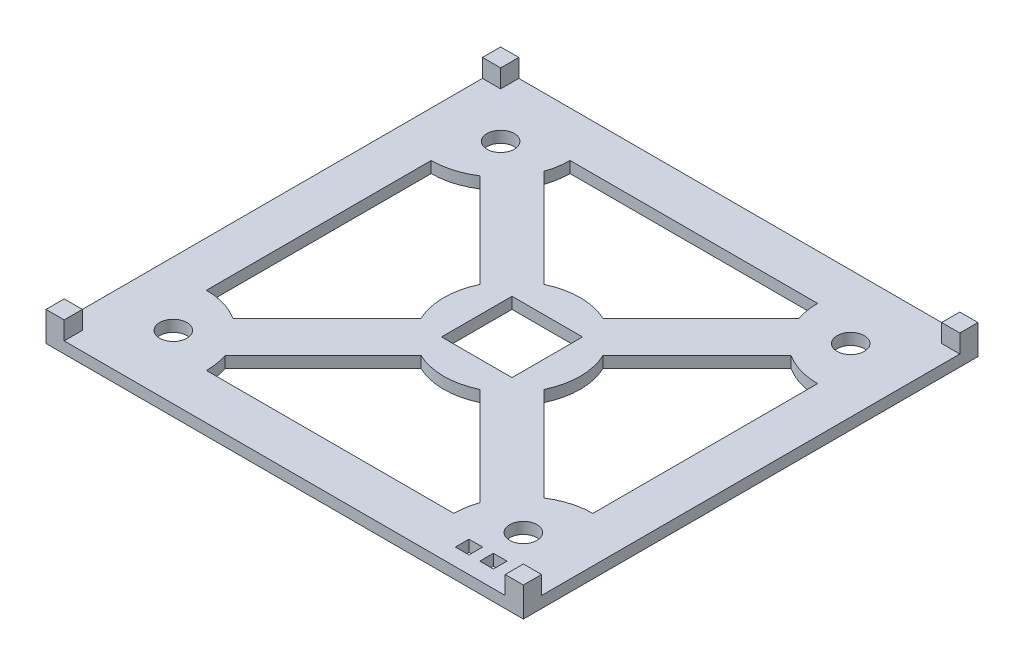
SolidWorks part; units mm, degrees
ref_plane "Front Plane" through (0, 0, 0) normal (0, 0, 1) x (1, 0, 0)
ref_plane "Top Plane" through (0, 0, 0) normal (0, 1, 0) x (1, 0, 0)
ref_plane "Right Plane" through (0, 0, 0) normal (1, 0, 0) x (0, 0, -1)
sketch "Sketch1" plane through (0, 0, 0) normal (0, 1, 0) x (1, 0, 0)
  line L1 (-52.5, -50) -> (52.5, -50)
  line L2 (-52.5, -50) -> (-52.5, 50)
  line L3 (-52.5, 50) -> (52.5, 50)
  line L4 (52.5, -50) -> (52.5, 50)
  line L5 (-52.5, -50) -> (52.5, 50) construction
  line L6 (-52.5, 50) -> (52.5, -50) construction
  point P0 (0, 0)
  dimension "D1" = 105
  dimension "D2" = 100
extrude "Boss-Extrude1" add sketch "Sketch1" along normal blind 2.5
sketch "Sketch3" plane through (0, 2.5, 0) normal (0, 1, 0) x (1, 0, 0)
  line L0 (-69.1295, 0) -> (69.1295, 0)
  line L1 (-52.5, 50) -> (-48.5, 50)
  line L2 (-52.5, 50) -> (-52.5, 46)
  line L3 (-52.5, 46) -> (-48.5, 46)
  line L4 (-48.5, 50) -> (-48.5, 46)
  line L5 (52.5, -50) -> (48.5, -50)
  line L6 (52.5, 50) -> (48.5, 50)
  line L7 (52.5, 50) -> (52.5, 46)
  line L8 (52.5, 46) -> (48.5, 46)
  line L9 (48.5, 50) -> (48.5, 46)
  line L10 (52.5, -50) -> (52.5, -46)
  line L11 (52.5, -46) -> (48.5, -46)
  line L12 (48.5, -50) -> (48.5, -46)
  line L13 (-48.5, -50) -> (-48.5, -46)
  line L14 (-52.5, -50) -> (-48.5, -50)
  line L15 (-52.5, -50) -> (-52.5, -46)
  line L16 (-52.5, -46) -> (-48.5, -46)
  point P9 (0, 0)
  line M14 (52.5, -50) -> (52.5, 50)
  line M15 (52.5, 50) -> (-52.5, 50)
  line M16 (-52.5, 50) -> (-52.5, -50)
  line M17 (-52.5, -50) -> (52.5, -50)
  dimension "D1" = 4
extrude "Boss-Extrude2" add sketch "Sketch3" along normal blind 4 contours L4 L3 M15 M16 | L9 L8 M15 M14 | L12 L11 M17 M14 | L16 L13 M16 M17
sketch "Sketch4" plane through (0, 2.5, 0) normal (0, 1, 0) x (1, 0, 0)
sketch "Sketch5" plane through (0, 2.5, 0) normal (0, 1, 0) x (1, 0, 0)
  line L1 (-42.5, -40) -> (42.5, -40)
  line L2 (-42.5, -40) -> (-42.5, 40)
  line L3 (-42.5, 40) -> (42.5, 40)
  line L4 (42.5, -40) -> (42.5, 40)
  line L5 (-42.5, -40) -> (42.5, 40) construction
  line L6 (-42.5, 40) -> (42.5, -40) construction
  line L7 (52.5, -46) -> (52.5, 46) construction
  line L8 (-48.5, -50) -> (48.5, -50) construction
  point P0 (0, 0)
  dimension "D1" = 10
  dimension "D2" = 10
extrude "Cut-Extrude2" cut sketch "Sketch5" against normal blind 4
sketch "Sketch6" plane through (0, 2.5, 0) normal (0, 1, 0) x (1, 0, 0)
  circle A0 centre (0, 0) radius 15
  dimension "D1" = 30
extrude "Boss-Extrude3" add sketch "Sketch6" against normal blind 2.5 separate body
sketch "Sketch7" plane through (0, 2.5, 0) normal (0, 1, 0) x (1, 0, 0)
  line L1 (-7.75, -7.75) -> (7.75, -7.75)
  line L2 (-7.75, -7.75) -> (-7.75, 7.75)
  line L3 (-7.75, 7.75) -> (7.75, 7.75)
  line L4 (7.75, -7.75) -> (7.75, 7.75)
  line L5 (-7.75, -7.75) -> (7.75, 7.75) construction
  line L6 (-7.75, 7.75) -> (7.75, -7.75) construction
  point P0 (0, 0)
  dimension "D1" = 15.5
  dimension "D2" = 15.5
extrude "Cut-Extrude3" cut sketch "Sketch7" against normal blind 2.5
sketch "Sketch8" plane through (0, 2.5, 0) normal (0, 1, 0) x (1, 0, 0)
  line L0 (42.5, -40) -> (42.5, 40) construction
  line L1 (42.5, 40) -> (-42.5, 40) construction
  line L2 (0, -54.2426) -> (0, 54.2426)
  line L3 (27.2201, 40) -> (42.5, 40)
  line L4 (42.5, 40) -> (42.5, 24.7201)
  line L5 (-63.2717, 0) -> (63.2717, 0)
  arc A0 (42.5, 24.7201) -> (27.2201, 40) centre (42.5, 40) cw
  arc A1 (-42.5, 24.7201) -> (-27.2201, 40) centre (-42.5, 40) ccw
  arc A2 (42.5, -24.7201) -> (27.2201, -40) centre (42.5, -40) ccw
  arc A3 (-42.5, -24.7201) -> (-27.2201, -40) centre (-42.5, -40) cw
  point P13 (0, 0)
  point P15 (0, 0)
  line M3 (-42.5, 40) -> (42.5, 40)
  line M4 (42.5, 40) -> (42.5, -40)
  line M5 (42.5, -40) -> (-42.5, -40)
  line M6 (-42.5, -40) -> (-42.5, 40)
extrude "Boss-Extrude4" add sketch "Sketch8" against normal blind 2.5 contours A3 M6 M5 | A1 M6 M3 | A0 M4 M3 | A2 M4 M5
sketch "Sketch9" plane through (0, 2.5, 0) normal (0, 1, 0) x (1, 0, 0)
  line L0 (7.75, -7.75) -> (38.0042, -38.0042)
  line L2 (-7.75, -7.75) -> (-38.0042, -38.0042)
  line L4 (7.75, 7.75) -> (38.0042, 38.0042)
  line L5 (-7.75, 7.75) -> (-38.0042, 38.0042)
  point P17 (0, 0)
  point P22 (0, 0)
extrude "Extrude-Thin2" add sketch "Sketch9" against normal blind 2.5 thin thin type mid plane wall 10
sketch "Sketch10" plane through (0, 2.5, 0) normal (0, 1, 0) x (1, 0, 0)
  line L0 (48.5, 50) -> (-48.5, 50) construction
  line L1 (52.5, -46) -> (52.5, 46) construction
  line L2 (-81.3718, 0) -> (93.495, 0) construction
  line L3 (0, 82.8678) -> (0, -87.0228) construction
  circle A0 centre (38.5, 36) radius 3
  circle A1 centre (-38.5, 36) radius 3
  circle A2 centre (38.5, -36) radius 3
  circle A3 centre (-38.5, -36) radius 3
  dimension "D1" = 6
  dimension "D2" = 14
  dimension "D3" = 14
extrude "Cut-Extrude5" cut sketch "Sketch10" against normal blind 2.5
sketch "Sketch11" plane through (0, 2.5, 0) normal (0, 1, 0) x (1, 0, 0)
  line L0 (37.9743, -39.1284) -> (37.9743, -49.44) construction
  line L1 (39.1573, -46.2521) -> (42.1573, -46.2521)
  line L2 (39.1573, -46.2521) -> (39.1573, -43.2521)
  line L3 (39.1573, -43.2521) -> (42.1573, -43.2521)
  line L4 (42.1573, -46.2521) -> (42.1573, -43.2521)
  line L5 (39.1573, -46.2521) -> (42.1573, -43.2521) construction
  line L6 (39.1573, -43.2521) -> (42.1573, -46.2521) construction
  line L7 (36.7914, -43.2521) -> (33.7914, -46.2521) construction
  line L8 (36.7914, -46.2521) -> (33.7914, -43.2521) construction
  line L9 (33.7914, -46.2521) -> (33.7914, -43.2521)
  line L10 (36.7914, -43.2521) -> (33.7914, -43.2521)
  line L11 (36.7914, -46.2521) -> (36.7914, -43.2521)
  line L12 (36.7914, -46.2521) -> (33.7914, -46.2521)
  point P0 (40.6573, -44.7521)
  point P11 (35.2914, -44.7521)
  dimension "D1" = 3
  dimension "D2" = 3
extrude "Cut-Extrude6" cut sketch "Sketch11" against normal blind 2.5
